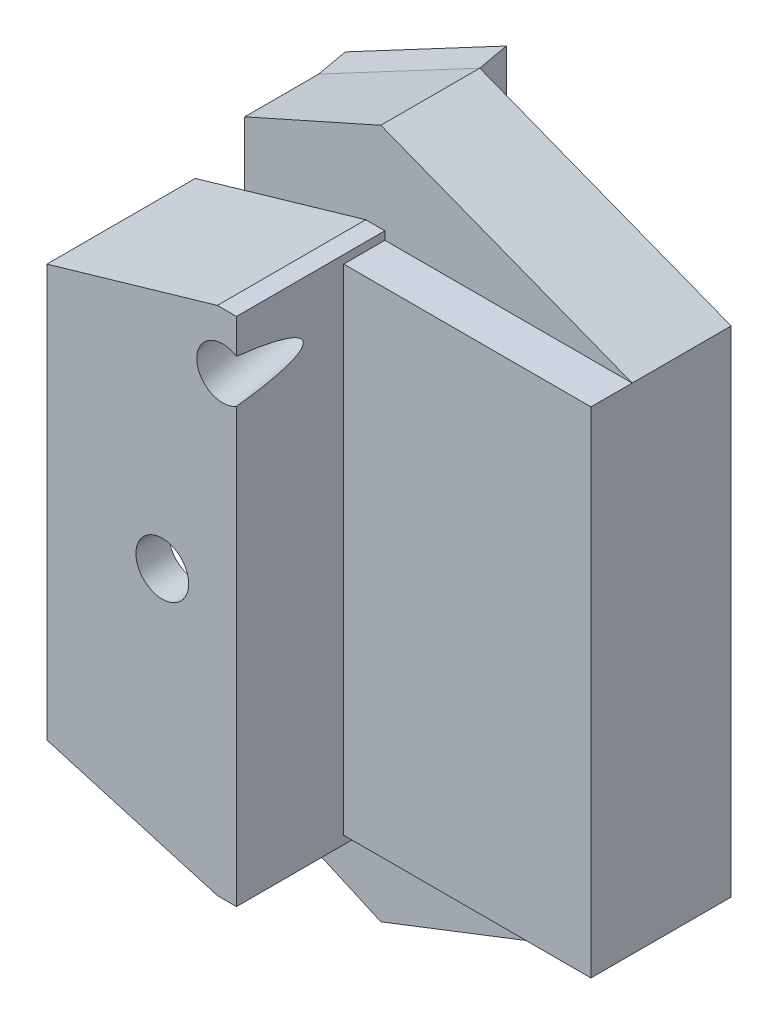
SolidWorks part; units mm, degrees
ref_plane "前视基准面" through (0, 0, 0) normal (0, 0, 1) x (1, 0, 0)
ref_plane "上视基准面" through (0, 0, 0) normal (0, 1, 0) x (1, 0, 0)
ref_plane "右视基准面" through (0, 0, 0) normal (1, 0, 0) x (0, 0, -1)
sketch "草图1" plane through (0, 0, 0) normal (0, 1, 0) x (1, 0, 0)
  line L0 (-2.8446, -2.6314) -> (-2.8446, 6.3686)
  line L4 (8.6554, 6.3686) -> (8.6554, -2.6314)
  line L5 (8.6554, -2.6314) -> (-2.8446, -2.6314)
  line L6 (-2.8446, 6.3686) -> (8.6554, 6.3686)
  dimension "D1" = 9
  dimension "D3" = 11.5
extrude "凸台-拉伸1" add sketch "草图1" along normal mid plane 31
sketch "草图3" plane through (0, 0, 2.6314) normal (0, 0, 1) x (1, 0, 0)
  line L0 (-2.8446, 15.5) -> (-2.8446, 12.5)
  line L1 (-2.8446, 15.5) -> (-2.8446, -15.5) construction
  line L2 (-2.8446, 12.5) -> (7.4964, 15.5)
  line L5 (7.4964, 15.5) -> (-2.8446, 15.5)
  line L6 (-9.7968, 0) -> (30.3279, 0) construction
  line L7 (7.4964, -15.5) -> (-2.8446, -15.5)
  line L8 (-2.8446, -12.5) -> (7.4964, -15.5)
  line L9 (-2.8446, -15.5) -> (-2.8446, -12.5)
  dimension "D1" = 3
extrude "切除-拉伸1" cut sketch "草图3" against normal up to next
sketch "草图6" plane through (-2.8446, 0, 0) normal (-1, 0, 0) x (0, 0, 1)
  line L1 (0.6314, 9.6657) -> (-6.3686, 9.6657)
  line L2 (0.6314, 9.6657) -> (0.6314, -9.6657)
  line L3 (0.6314, -9.6657) -> (-6.3686, -9.6657)
  line L5 (0.6314, 9.6657) -> (-6.3686, -9.6657) construction
  line L6 (0.6314, -9.6657) -> (-6.3686, 9.6657) construction
  line L7 (-6.3686, -9.6657) -> (-11.2629, -9.6657)
  line L8 (-11.2629, -9.6657) -> (-11.2629, 9.6657)
  line L9 (-11.2629, 9.6657) -> (-6.3686, 9.6657)
  point P0 (-2.8686, 0)
  dimension "D1" = 7
extrude "切除-拉伸3" cut sketch "草图6" against normal blind 10
sketch "草图7" plane through (0, 0, 0.6314) normal (0, 0, -1) x (-1, 0, 0)
  line L0 (2.8446, -9.6657) -> (2.8446, 9.6657) construction
  circle A0 centre (-4.1554, 0) radius 1.6
  dimension "D2" = 3.2
  dimension "D1" = 7
extrude "切除-拉伸4" cut sketch "草图7" against normal blind 3.2
sketch "草图8" plane through (0, 0, 2.6314) normal (0, 0, 1) x (1, 0, 0)
  line L0 (7.4964, -15.5) -> (8.6554, -15.5) construction
  line L1 (8.0759, -15.5) -> (9.1017, -15.5)
  line L2 (8.0759, -15.5) -> (8.0759, 15.5)
  line L3 (8.0759, 15.5) -> (9.1017, 15.5)
  line L4 (9.1017, -15.5) -> (9.1017, 15.5)
sketch "草图9" plane through (0, 0, 0) normal (0, 1, 0) x (1, 0, 0)
  line L1 (8.6554, 6.3686) -> (23.6554, 6.3686)
  line L2 (8.6554, 6.3686) -> (8.6554, 3.8686)
  line L3 (8.6554, 3.8686) -> (23.6554, 3.8686)
  line L4 (23.6554, 6.3686) -> (23.6554, 3.8686)
  dimension "D1" = 2.5
  dimension "D2" = 15
extrude "凸台-拉伸2" add sketch "草图9" along normal mid plane 30
sketch "草图10" plane through (0, 0, -6.3686) normal (0, 0, -1) x (-1, 0, 0)
  line L0 (2.8446, 9.6657) -> (2.8446, 15.8984)
  line L1 (2.8446, 15.8984) -> (-8.4113, 20.9203)
  line L2 (-8.4113, 20.9203) -> (-23.6554, 15)
  line L3 (-23.6554, 15) -> (-23.6554, -15)
  line L4 (-23.6554, 15) -> (-23.6554, -15) construction
  line L5 (-23.6554, 0) -> (-7.1554, 0)
  line L6 (-7.1554, -9.6657) -> (-7.1554, 9.6657) construction
  line L7 (-7.1554, -9.6657) -> (-7.1554, 9.6657)
  line L8 (-7.1554, 9.6657) -> (2.8446, 9.6657)
  line L9 (11.9901, 0) -> (-36.2409, 0) construction
  line L10 (-7.1554, -9.6657) -> (2.8446, -9.6657)
  line L11 (2.8446, -9.6657) -> (2.8446, -15.8984)
  line L12 (2.8446, -15.8984) -> (-8.4113, -20.9203)
  line L13 (-8.4113, -20.9203) -> (-23.6554, -15)
extrude "凸台-拉伸3" add sketch "草图10" along normal blind 6 contours L2 L3 L13 L12 L11 L10 L7 L8 L0 L1
sketch "草图11" plane through (0, 0, 0) normal (0, 1, 0) x (1, 0, 0)
  line L0 (8.4113, 12.3686) -> (0.1554, 10.8601)
  line L1 (-2.8446, 12.3686) -> (-2.8446, 6.3686) construction
  line L2 (-2.8446, 10.3686) -> (-2.8446, 12.3686)
  line L3 (-2.8446, 12.3686) -> (8.4113, 12.3686)
  line L4 (-2.8446, 10.3686) -> (-2.8446, 6.3686)
  line L5 (-2.8446, 6.3686) -> (0.1554, 6.3686)
  line L6 (-2.8446, 6.3686) -> (8.4113, 6.3686) construction
  line L7 (0.1554, 6.3686) -> (0.1554, 10.8601)
  dimension "D1" = 2
  dimension "D2" = 3
extrude "切除-拉伸5" cut sketch "草图11" against normal mid plane 50
sketch "草图12" plane through (-1.9153, 0, -10.4817) normal (-0.1797, 0, -0.9837) x (-0.9837, 0, 0.1797)
  circle A0 centre (-7.2199, 12.0907) radius 1.55
extrude "切除-拉伸6" cut sketch "草图12" against normal blind 50
sketch "草图13" plane through (-1.9153, 0, -10.4817) normal (-0.1797, 0, -0.9837) x (-0.9837, 0, 0.1797)
  line L0 (-10.4975, 20.9203) -> (-10.4975, 16.9203)
  line L1 (-10.4975, 20.9203) -> (-10.4975, -20.9203) construction
  line L2 (-10.4975, 16.9203) -> (-2.105, 16.9203)
  line L3 (-2.105, 9.6657) -> (-2.105, 17.2369) construction
  line L4 (-2.105, 16.9203) -> (-2.105, 17.2369)
  line L5 (-2.105, 17.2369) -> (-10.4975, 20.9203)
  line L6 (-10.4975, -20.9203) -> (-10.4975, -16.9203)
  line L7 (-10.4975, -16.9203) -> (-2.105, -16.9203)
  line L8 (-2.105, -17.2369) -> (-2.105, -9.6657) construction
  line L9 (-2.105, -16.9203) -> (-2.105, -17.2369)
  line L10 (-2.105, -17.2369) -> (-10.4975, -20.9203)
  dimension "D1" = 4
  dimension "D2" = 4
extrude "凸台-拉伸4" add sketch "草图13" along normal blind 2
